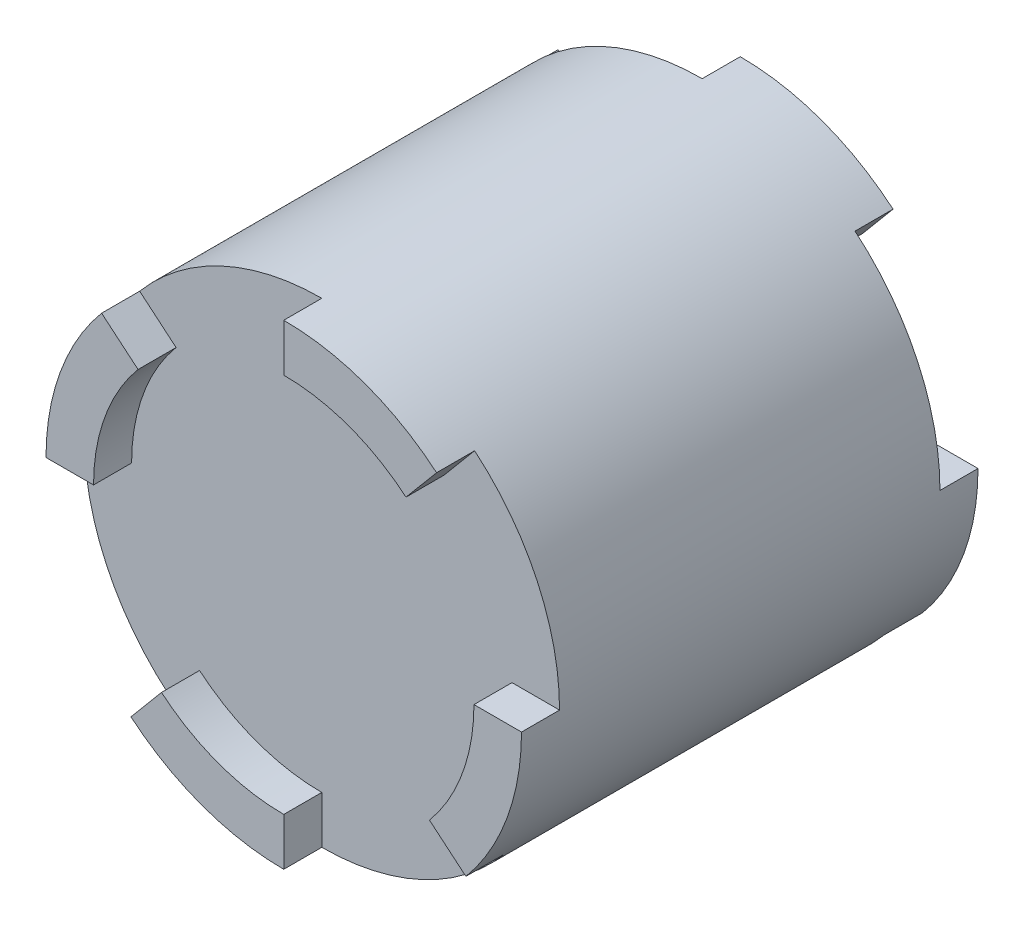
SolidWorks part; units mm, degrees
ref_plane "Front Plane" through (0, 0, 0) normal (0, 0, 1) x (1, 0, 0)
ref_plane "Top Plane" through (0, 0, 0) normal (0, 1, 0) x (1, 0, 0)
ref_plane "Right Plane" through (0, 0, 0) normal (1, 0, 0) x (0, 0, -1)
sketch "Sketch1" plane through (0, 0, 0) normal (0, 0, 1) x (1, 0, 0)
  circle A0 centre (0, 0) radius 25
  dimension "D1" = 50
extrude "Boss-Extrude1" add sketch "Sketch1" along normal mid plane 40
sketch "Sketch2" plane through (0, 0, 20) normal (0, 0, 1) x (1, 0, 0)
  line L0 (0, 0) -> (0, 25) construction
  line L1 (0, 0) -> (25, 0) construction
  line L2 (25, 0) -> (0, 0) construction
  line L3 (0, 0) -> (0, -25) construction
  line L4 (0, -25) -> (0, 0) construction
  line L5 (0, 0) -> (-25, 0) construction
  line L6 (0, 0) -> (-19.1511, 16.0697) construction
  line L7 (0, 0) -> (16.0697, 19.1511) construction
  line L8 (0, 0) -> (19.1511, -16.0697) construction
  line L9 (0, 0) -> (-16.0697, -19.1511) construction
  line L10 (-25, 0) -> (-20, 0)
  line L11 (-19.1511, 16.0697) -> (-15.3209, 12.8558)
  line L12 (16.0697, 19.1511) -> (12.8558, 15.3209)
  line L13 (0, 25) -> (0, 20)
  line L14 (25, 0) -> (20, 0)
  line L15 (19.1511, -16.0697) -> (15.3209, -12.8558)
  line L16 (0, -20) -> (0, -25)
  line L17 (-12.8558, -15.3209) -> (-16.0697, -19.1511)
  arc A0 (-15.3209, 12.8558) -> (-20, 0) centre (0, 0) ccw
  circle A1 centre (0, 0) radius 25 construction
  arc A2 (-19.1511, 16.0697) -> (-25, 0) centre (0, 0) ccw
  arc A3 (16.0697, 19.1511) -> (0, 25) centre (0, 0) ccw
  arc A4 (12.8558, 15.3209) -> (0, 20) centre (0, 0) ccw
  arc A5 (19.1511, -16.0697) -> (25, 0) centre (0, 0) ccw
  arc A6 (15.3209, -12.8558) -> (20, 0) centre (0, 0) ccw
  arc A7 (-16.0697, -19.1511) -> (0, -25) centre (0, 0) ccw
  arc A8 (-12.8558, -15.3209) -> (0, -20) centre (0, 0) ccw
  dimension "D1" = 20
  dimension "D2" = 40
extrude "Boss-Extrude2" add sketch "Sketch2" along normal blind 4
mirror "Mirror1" about plane through (0, 0, 0) normal (0, 0, 1) of "Boss-Extrude2"
